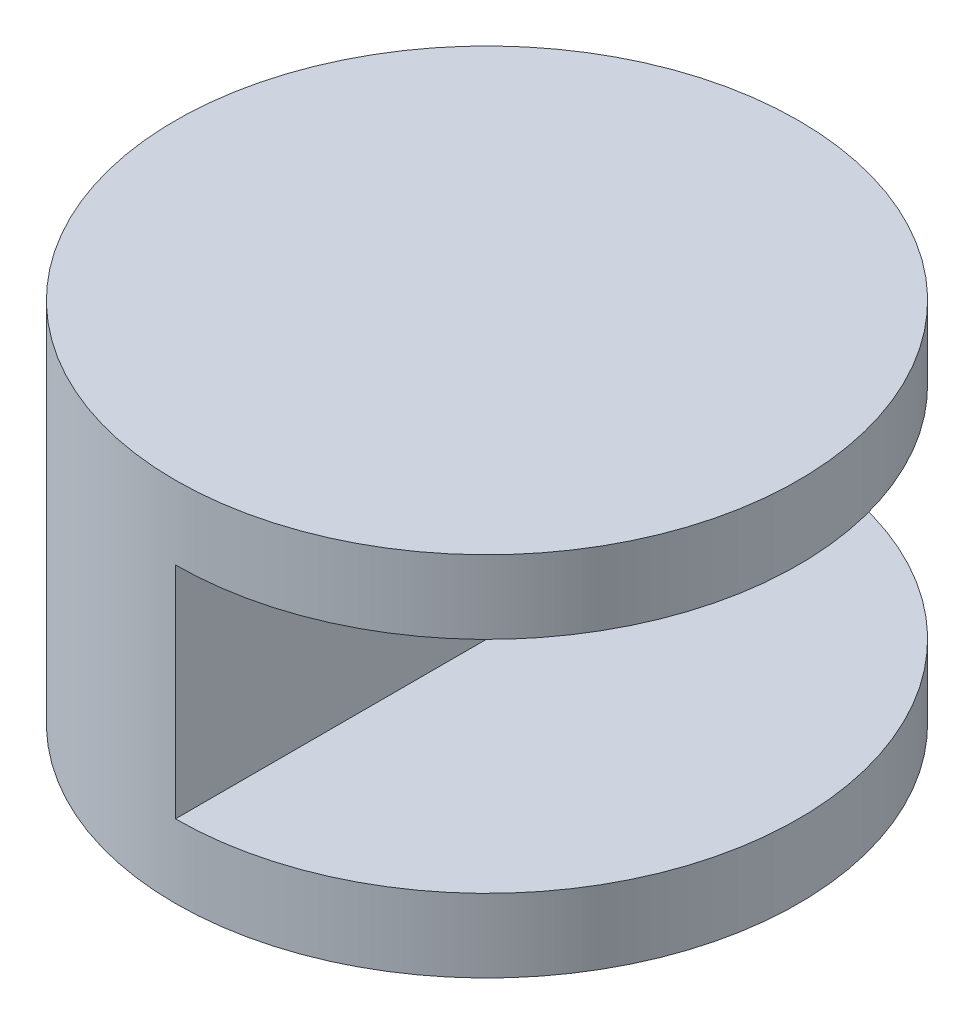
SolidWorks part; units mm, degrees
ref_plane "Front Plane" through (0, 0, 0) normal (0, 0, 1) x (1, 0, 0)
ref_plane "Top Plane" through (0, 0, 0) normal (0, 1, 0) x (1, 0, 0)
ref_plane "Right Plane" through (0, 0, 0) normal (1, 0, 0) x (0, 0, -1)
sketch "Sketch1" plane through (0, 0, 0) normal (0, 1, 0) x (1, 0, 0)
  circle A0 centre (0, 0) radius 12.7
  dimension "D1" = 25.4
sketch "Sketch2" plane through (0, 0, 0) normal (0, 1, 0) x (1, 0, 0)
  circle A0 centre (0, 0) radius 10.795
  dimension "D1" = 21.59
extrude "Boss-Extrude1" add sketch "Sketch2" against normal blind 12.7
sketch "Sketch3" plane through (0, 0, 0) normal (1, 0, 0) x (0, 0, -1)
  line L0 (12.7, 0) -> (-12.7, 0) construction
  line L1 (-13.6481, -2.54) -> (11.7912, -2.54)
  line L2 (-13.6481, -2.54) -> (-13.6481, -10.16)
  line L3 (-13.6481, -10.16) -> (11.7912, -10.16)
  line L4 (11.7912, -2.54) -> (11.7912, -10.16)
  dimension "D1" = 2.54
  dimension "D2" = 7.62
  dimension "D3" = 25.4393
extrude "Cut-Extrude1" cut sketch "Sketch3" along normal through all contours L4 L3 L2 L1
sketch "Sketch5" plane through (0, 0, 0) normal (0, 1, 0) x (1, 0, 0)
  circle A0 centre (8.636, 0) radius 1.27
  dimension "D1" = 2.54
  dimension "D2" = 8.636
equation "\"D1@Sketch7\" = \"D1@Sketch1\" / 10"
equation "\"D2@Sketch7\" = ( \"D1@Sketch1\" / 2 ) - ( \"D1@Sketch7\" * 1.6 )"
equation "\"D1@Sketch2\" = \"D1@Sketch1\" * 0.85"
equation "\"D2@Sketch3\" = \"D1@Boss-Extrude1\" * 3 / 5"
equation "\"D1@Sketch3\" = \"D1@Boss-Extrude1\" / 5"
equation "\"D1@Sketch5\" = ( \"D1@Sketch1\" / 10 )"
equation "\"D2@Sketch5\" = ( \"D1@Sketch1\" / 2 ) - ( \"D1@Sketch5\" * 1.6 )"
